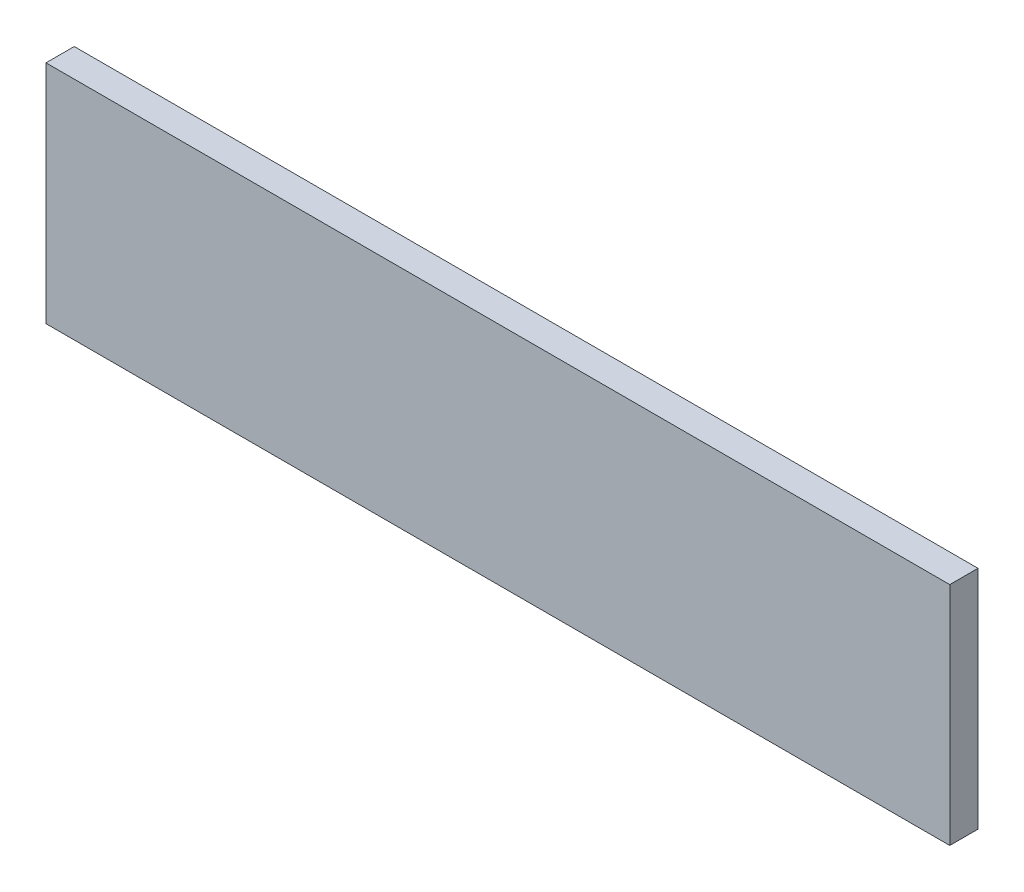
SolidWorks part; units mm, degrees
ref_plane "Front Plane" through (0, 0, 0) normal (0, 0, 1) x (1, 0, 0)
ref_plane "Top Plane" through (0, 0, 0) normal (0, 1, 0) x (1, 0, 0)
ref_plane "Right Plane" through (0, 0, 0) normal (1, 0, 0) x (0, 0, -1)
sketch "Sketch1" plane through (0, 0, 0) normal (0, 0, 1) x (1, 0, 0)
  line L1 (0, 0) -> (203.2, 0)
  line L2 (0, 0) -> (0, 50.8)
  line L3 (0, 50.8) -> (203.2, 50.8)
  line L4 (203.2, 0) -> (203.2, 50.8)
  dimension "D1" = 50.8
  dimension "D2" = 203.2
extrude "Boss-Extrude1" add sketch "Sketch1" along normal blind 6.35
